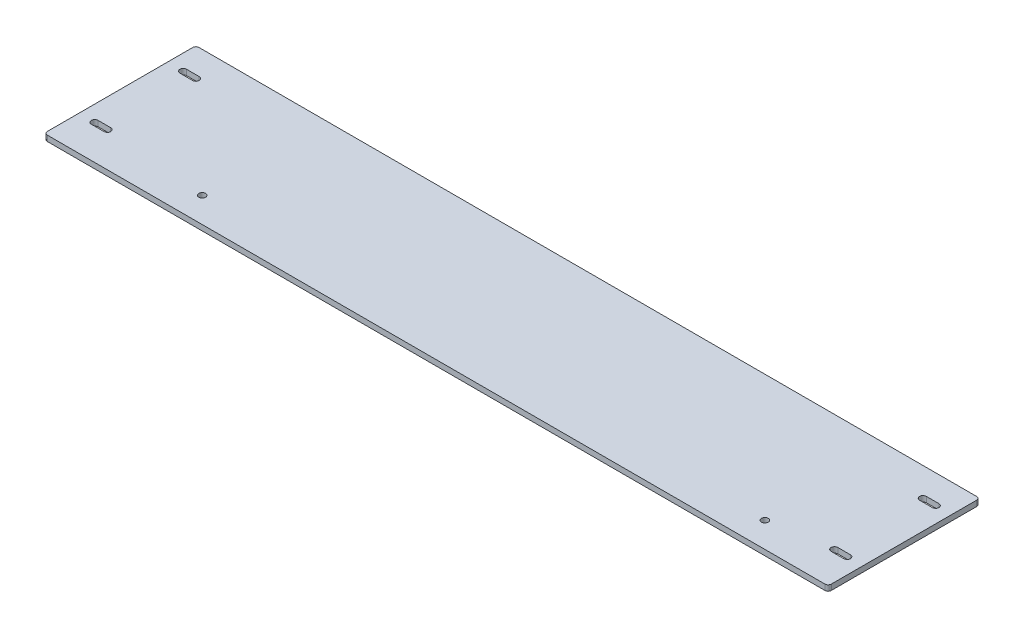
SolidWorks part; units mm, degrees
material "PC High Viscosity"
ref_plane "Front" through (0, 0, 0) normal (0, 0, 1) x (1, 0, 0)
ref_plane "Top" through (0, 0, 0) normal (0, 1, 0) x (1, 0, 0)
ref_plane "Right" through (0, 0, 0) normal (1, 0, 0) x (0, 0, -1)
sketch "Sketch1" plane through (0, 0, 0) normal (0, 1, 0) x (1, 0, 0)
  line L0 (15.875, 34.925) -> (28.575, 34.925) construction
  line L1 (0, 0) -> (787.4, 0)
  line L2 (0, 0) -> (0, 152.4)
  line L3 (0, 152.4) -> (787.4, 152.4)
  line L4 (787.4, 0) -> (787.4, 152.4)
  line L5 (15.875, 38.3032) -> (28.575, 38.3032)
  line L6 (15.875, 31.5468) -> (28.575, 31.5468)
  line L7 (22.225, 34.925) -> (22.225, 123.825) construction
  line L8 (15.875, 123.825) -> (28.575, 123.825) construction
  line L9 (15.875, 127.2032) -> (28.575, 127.2032)
  line L10 (15.875, 120.4468) -> (28.575, 120.4468)
  line L11 (22.225, 123.825) -> (66.675, 123.825) construction
  line L12 (66.675, 123.825) -> (66.675, 34.925) construction
  line L13 (66.675, 34.925) -> (22.225, 34.925) construction
  line L14 (60.325, 123.825) -> (73.025, 123.825) construction
  line L15 (60.325, 127.2032) -> (73.025, 127.2032) construction
  line L16 (60.325, 120.4468) -> (73.025, 120.4468) construction
  line L17 (60.325, 34.925) -> (73.025, 34.925) construction
  line L18 (60.325, 38.3032) -> (73.025, 38.3032) construction
  line L19 (60.325, 31.5468) -> (73.025, 31.5468) construction
  line L20 (765.175, 123.825) -> (765.175, 34.925) construction
  line L21 (771.525, 123.825) -> (758.825, 123.825) construction
  line L22 (771.525, 120.4468) -> (758.825, 120.4468)
  line L23 (771.525, 127.2032) -> (758.825, 127.2032)
  line L24 (771.525, 34.925) -> (758.825, 34.925) construction
  line L25 (771.525, 31.5468) -> (758.825, 31.5468)
  line L26 (771.525, 38.3032) -> (758.825, 38.3032)
  arc A0 (15.875, 38.3032) -> (15.875, 31.5468) centre (15.875, 34.925) ccw
  arc A1 (28.575, 31.5468) -> (28.575, 38.3032) centre (28.575, 34.925) ccw
  arc A2 (15.875, 127.2032) -> (15.875, 120.4468) centre (15.875, 123.825) ccw
  arc A3 (28.575, 120.4468) -> (28.575, 127.2032) centre (28.575, 123.825) ccw
  arc A4 (60.325, 127.2032) -> (60.325, 120.4468) centre (60.325, 123.825) ccw construction
  arc A5 (73.025, 120.4468) -> (73.025, 127.2032) centre (73.025, 123.825) ccw construction
  arc A6 (60.325, 38.3032) -> (60.325, 31.5468) centre (60.325, 34.925) ccw construction
  arc A7 (73.025, 31.5468) -> (73.025, 38.3032) centre (73.025, 34.925) ccw construction
  arc A8 (771.525, 120.4468) -> (771.525, 127.2032) centre (771.525, 123.825) ccw
  arc A9 (758.825, 127.2032) -> (758.825, 120.4468) centre (758.825, 123.825) ccw
  arc A10 (771.525, 31.5468) -> (771.525, 38.3032) centre (771.525, 34.925) ccw
  arc A11 (758.825, 38.3032) -> (758.825, 31.5468) centre (758.825, 34.925) ccw
  point P7 (22.225, 34.925)
  point P13 (22.225, 123.825)
  point P25 (66.675, 123.825)
  point P31 (66.675, 34.925)
  point P40 (765.175, 123.825)
  point P47 (765.175, 34.925)
  dimension "D1" = 6.7564
  dimension "D2" = 34.925
  dimension "D3" = 12.7
  dimension "D4" = 22.225
  dimension "D5" = 28.575
  dimension "D6" = 152.4
  dimension "D7" = 44.45
  dimension "D8" = 22.225
  dimension "D9" = 698.5
extrude "Boss-Extrude1" add sketch "Sketch1" along normal blind 5.588
fillet "Fillet1" radius 3.175 4 edges at (0, 2.794, -152.4) (787.4, 2.794, -152.4) (0, 2.794, 0) (787.4, 2.794, 0)
sketch "Sketch2" plane through (0, 5.588, 0) normal (0, 1, 0) x (1, 0, 0)
  line L0 (0, 76.2) -> (787.4, 76.2) construction
  line L1 (0, 149.225) -> (0, 3.175) construction
  line L2 (787.4, 3.175) -> (787.4, 149.225) construction
  line L3 (784.225, 152.4) -> (3.175, 152.4) construction
  line L4 (133.35, 25.4) -> (698.5, 25.4) construction
  line L5 (133.35, 25.4) -> (133.35, 127) construction
  line L6 (133.35, 127) -> (698.5, 127) construction
  line L7 (698.5, 25.4) -> (698.5, 127) construction
  line L8 (133.35, 25.4) -> (698.5, 127) construction
  line L9 (133.35, 127) -> (698.5, 25.4) construction
  circle A1 centre (133.35, 25.4) radius 3.3782
  circle A2 centre (698.5, 25.4) radius 3.3782
  point P6 (415.925, 76.2)
  dimension "D2" = 6.7564
  dimension "D1" = 88.9
  dimension "D3" = 25.4
  dimension "D4" = 565.15
extrude "Cut-Extrude1" cut sketch "Sketch2" against normal through all
